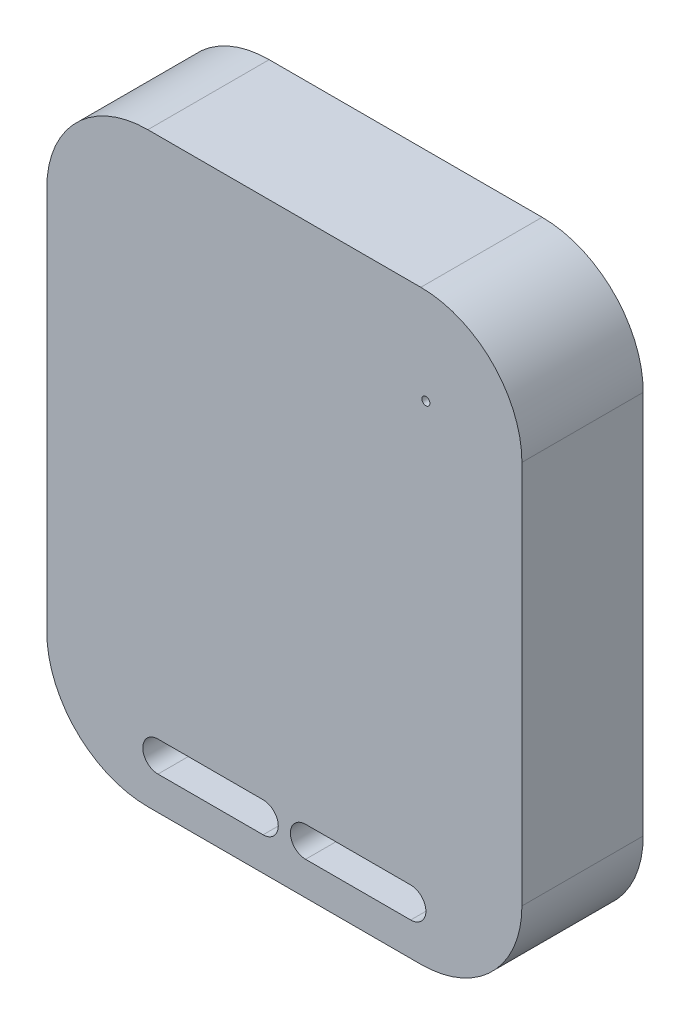
SolidWorks part; units mm, degrees
ref_plane "前视基准面" through (0, 0, 0) normal (0, 0, 1) x (1, 0, 0)
ref_plane "上视基准面" through (0, 0, 0) normal (0, 1, 0) x (1, 0, 0)
ref_plane "右视基准面" through (0, 0, 0) normal (1, 0, 0) x (0, 0, -1)
sketch "草图1" plane through (0, 0, 0) normal (0, 0, 1) x (1, 0, 0)
  line L0 (-13.5, 29) -> (13.5, 29)
  line L1 (23.5, 19) -> (23.5, -19)
  line L2 (13.5, -29) -> (-13.5, -29)
  line L3 (-23.5, -19) -> (-23.5, 19)
  arc A0 (13.5, 29) -> (23.5, 19) centre (13.5, 19) cw
  arc A1 (23.5, -19) -> (13.5, -29) centre (13.5, -19) cw
  arc A2 (-13.5, -29) -> (-23.5, -19) centre (-13.5, -19) cw
  arc A3 (-23.5, 19) -> (-13.5, 29) centre (-13.5, 19) cw
extrude "Pocket_Tag_body_58x47x12_R10" add sketch "草图1" along normal blind 12
sketch "草图2" plane through (0, 0, 0) normal (0, 0, 1) x (1, 0, 0)
  line L0 (-12.5, -22.7) -> (-2.1, -22.7)
  line L1 (-2.1, -25.7) -> (-12.5, -25.7)
  arc A0 (-2.1, -22.7) -> (-2.1, -25.7) centre (-2.1, -24.2) cw
  arc A1 (-12.5, -25.7) -> (-12.5, -22.7) centre (-12.5, -24.2) cw
extrude "Lanyard_slot_left_real" cut sketch "草图2" along normal blind 12.5
sketch "草图3" plane through (0, 0, 0) normal (0, 0, 1) x (1, 0, 0)
  line L0 (2.1, -22.7) -> (12.5, -22.7)
  line L1 (12.5, -25.7) -> (2.1, -25.7)
  arc A0 (12.5, -22.7) -> (12.5, -25.7) centre (12.5, -24.2) cw
  arc A1 (2.1, -25.7) -> (2.1, -22.7) centre (2.1, -24.2) cw
extrude "Lanyard_slot_right_real" cut sketch "草图3" along normal blind 12.5
sketch "草图4" plane through (0, 0, 0) normal (0, 0, 1) x (1, 0, 0)
  circle A0 centre (14, 19.5) radius 0.4
extrude "Status_LED_hole_real" cut sketch "草图4" along normal blind 12.5
sketch "草图5" plane through (0, 0, 0) normal (0, 0, -1) x (-1, 0, 0)
  line L0 (-2.9, 1.6) -> (2.9, 1.6)
  line L1 (2.9, -1.6) -> (-2.9, -1.6)
  arc A0 (2.9, 1.6) -> (2.9, -1.6) centre (2.9, 0) cw
  arc A1 (-2.9, -1.6) -> (-2.9, 1.6) centre (-2.9, 0) cw
extrude "USB_C_side_opening_9x3_2_at_PCB_USB1" cut sketch "草图5" against normal blind 5
sketch "草图6" plane through (0, 0, 0) normal (0, 0, 1) x (1, 0, 0)
  line L0 (-19, 20.9) -> (-17.4, 21.7)
  line L1 (-17.4, 21.7) -> (-17.4, 25.1)
  line L2 (-17.4, 25.1) -> (-19, 24.3)
  line L3 (-19, 24.3) -> (-19, 20.9)
extrude "Direction_marker_recess" cut sketch "草图6" along normal blind 0.22
sketch "草图7" plane through (0, 0, 0) normal (0, 0, 1) x (1, 0, 0)
  text T0 "POYU" font "Arial" height 5
extrude "Engraved_Logo_POYU" cut sketch "草图7" along normal blind 0.28
sketch "草图8" plane through (0, 0, 0) normal (0, 0, 1) x (1, 0, 0)
  text T0 "Pocket Tag" font "Arial" height 2.1
extrude "Engraved_Logo_Pocket_Tag" cut sketch "草图8" along normal blind 0.22
